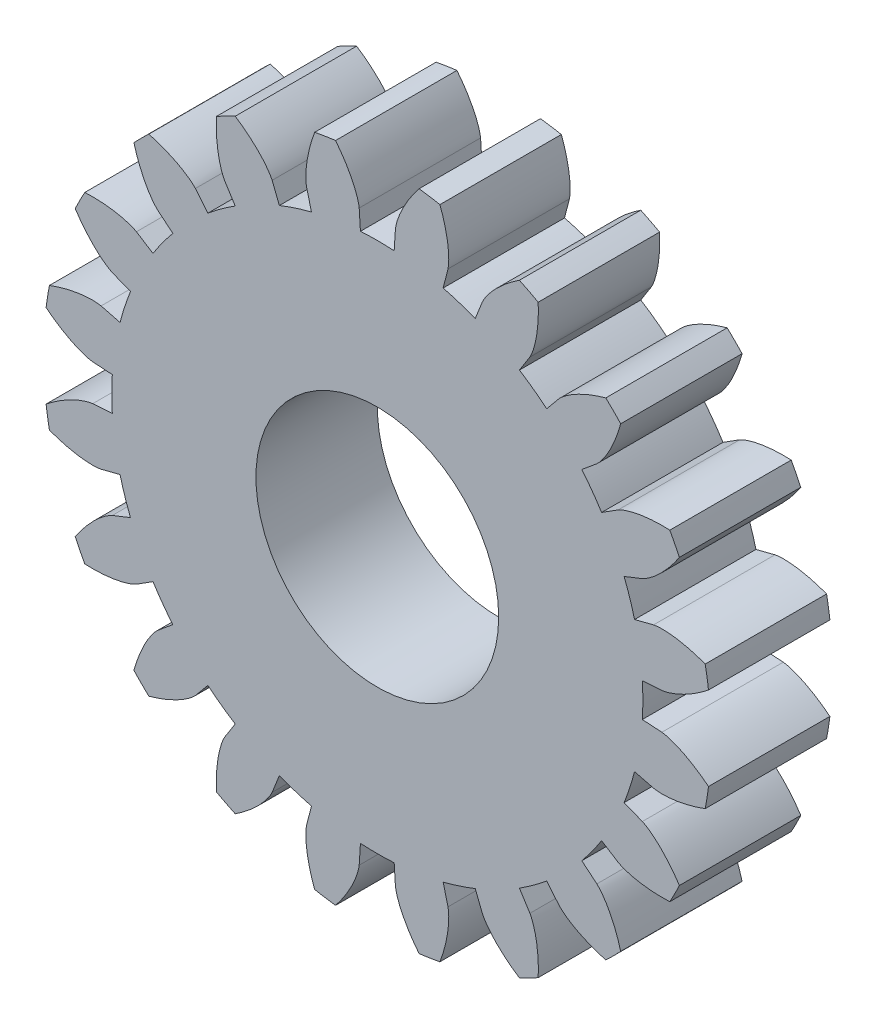
SolidWorks part; units mm, degrees
ref_plane "Front Plane" through (0, 0, 0) normal (0, 0, 1) x (1, 0, 0)
ref_plane "Top Plane" through (0, 0, 0) normal (0, 1, 0) x (1, 0, 0)
ref_plane "Right Plane" through (0, 0, 0) normal (1, 0, 0) x (0, 0, -1)
sketch "Sketch1" plane through (0, 0, 0) normal (0, 0, 1) x (1, 0, 0)
  circle A0 centre (0, 0) radius 27.5
  dimension "GearOverall" = 55
extrude "Boss-Extrude1" add sketch "Sketch1" along normal mid plane 10
sketch "Sketch2" plane through (0, 0, 5) normal (0, 0, 1) x (1, 0, 0)
  line L0 (0, 0) -> (0, 27.5) construction
  line L1 (0, 0) -> (-27.5, 0) construction
  line L2 (-1.4922, 23.4426) -> (0, 0) construction
  line L3 (0, 0) -> (-3.9344, 23.1582) construction
  line L4 (-3.9344, 23.1582) -> (-1.5092, 23.5702) construction
  line L5 (0, 0) -> (-6.3336, 22.62) construction
  line L6 (-6.3336, 22.62) -> (-1.5958, 23.9466) construction
  line L7 (0, 0) -> (-8.6633, 21.8341) construction
  line L8 (-8.6633, 21.8341) -> (-1.8036, 24.5559) construction
  line L9 (0, 0) -> (-10.8981, 20.8089) construction
  line L10 (-10.8981, 20.8089) -> (-2.1812, 25.3742) construction
  line L11 (0, 0) -> (-13.0136, 19.5558) construction
  line L12 (-13.0136, 19.5558) -> (-2.7736, 26.37) construction
  line L13 (0, 0) -> (-14.9864, 18.0883) construction
  line L14 (-14.9864, 18.0883) -> (-3.6205, 27.5051) construction
  line L15 (0, 0) -> (-16.795, 16.4227) construction
  line L16 (-16.795, 16.4227) -> (-4.7559, 28.7348) construction
  circle A0 centre (0, 0) radius 27.5 construction
  circle A1 centre (0, 0) radius 23.49 construction
  circle A2 centre (0, 0) radius 25 construction
  arc A3 (0, 23.49) -> (-1.4922, 23.4426) centre (0, 0) ccw construction
  arc A4 (-1.4922, 23.4426) -> (1.4922, 23.4426) centre (0, 0) cw
  arc A5 (-4.7559, 28.7348) -> (4.7559, 28.7348) centre (0, 1.6492) cw
  spline S0 degree 3 poles (-1.4922, 23.4426) (-1.5097, 23.6135) (-1.5981, 23.9909) (-1.823, 24.6405) (-2.2058, 25.4584) (-3.0904, 26.9331) (-4.0211, 28.0142) (-4.7559, 28.7348) knots 0 0 0 0 0.081636 0.183677 0.326533 0.510206 1 1 1 1
  spline S1 degree 3 poles (1.4922, 23.4426) (1.5097, 23.6135) (1.5981, 23.9909) (1.823, 24.6405) (2.2058, 25.4584) (3.0904, 26.9331) (4.0211, 28.0142) (4.7559, 28.7348) knots 0 0 0 0 0.081636 0.183677 0.326533 0.510206 1 1 1 1
  point P14 (-1.96, 24.923)
  dimension "BaseCircle" = 46.98
  dimension "PCD" = 50
  dimension "MirrorDist" = 1.96
  dimension "D2" = 6
  dimension "InvoluteGAP" = 2.46
  dimension "D3" = 4.92
  dimension "D4" = 6
  dimension "D5" = 7.38
  dimension "D6" = 6
  dimension "D7" = 9.84
  dimension "D8" = 6
  dimension "D9" = 12.3
  dimension "D10" = 6
  dimension "D11" = 14.76
  dimension "D12" = 6
  dimension "D13" = 17.22
  dimension "D14" = 6
extrude "Cut-Extrude1" cut sketch "Sketch2" against normal through all contours A5 S1 A4 S0
sketch "Sketch4" plane through (0, 0, 5) normal (0, 0, 1) x (1, 0, 0)
  line L0 (0, 0) -> (-1.4922, 23.4426)
  line L1 (0, 0) -> (1.4922, 23.4426)
  arc A0 (1.4922, 23.4426) -> (-1.4922, 23.4426) centre (0, 0) ccw construction
  arc A1 (1.4922, 23.4426) -> (-1.4922, 23.4426) centre (0, 0) ccw
  circle A2 centre (0, 0) radius 21.875
  arc M1 (1.4922, 23.4426) -> (-1.4922, 23.4426) centre (0, 0) ccw
  dimension "Dedendum" = 43.75
extrude "Cut-Extrude2" cut sketch "Sketch4" against normal through all contours A2 L1 L0 M1
pattern_circular "CirPattern1" count 20 over 360 about axis through (0, 0, 5) along (0, 0, -1) of "Cut-Extrude1", "Cut-Extrude2"
sketch "Sketch5" plane through (0, 0, 5) normal (0, 0, 1) x (1, 0, 0)
  circle A0 centre (0, 0) radius 10
  dimension "ID" = 20
extrude "Cut-Extrude3" cut sketch "Sketch5" against normal through all
equation "\"D3@Sketch2\" = \"InvoluteGAP@Sketch2\" * 2"
equation "\"D5@Sketch2\" = \"InvoluteGAP@Sketch2\" * 3"
equation "\"D7@Sketch2\" = \"InvoluteGAP@Sketch2\" * 4"
equation "\"D9@Sketch2\" = \"InvoluteGAP@Sketch2\" * 5"
equation "\"D11@Sketch2\" = \"InvoluteGAP@Sketch2\" * 6"
equation "\"D13@Sketch2\" = \"InvoluteGAP@Sketch2\" * 7"
